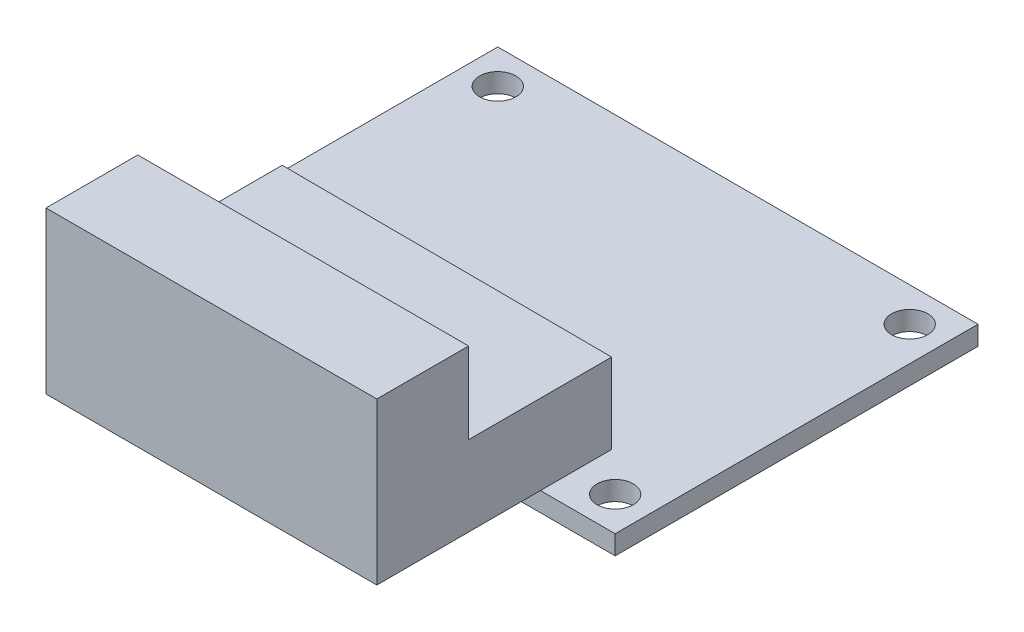
SolidWorks part; units mm, degrees
ref_plane "Front" through (0, 0, 0) normal (0, 0, 1) x (1, 0, 0)
ref_plane "Top" through (0, 0, 0) normal (0, 1, 0) x (1, 0, 0)
ref_plane "Right" through (0, 0, 0) normal (1, 0, 0) x (0, 0, -1)
sketch "Szkic1" plane through (0, 0, 0) normal (0, 1, 0) x (1, 0, 0)
  line L1 (-25.4695, 15.2387) -> (19.5305, 15.2387)
  line L2 (-25.4695, 15.2387) -> (-25.4695, -18.7613)
  line L3 (-25.4695, -18.7613) -> (19.5305, -18.7613)
  line L4 (19.5305, 15.2387) -> (19.5305, -18.7613)
  dimension "D1" = 45
  dimension "D2" = 34
extrude "Dodanie-wyciągnięcie1" add sketch "Szkic1" along normal blind 1.8
sketch "Szkic2" plane through (0, 1.8, 0) normal (0, 1, 0) x (1, 0, 0)
  line L0 (-25.4695, 15.2387) -> (-25.4695, -18.7613) construction
  line L1 (-25.4695, -18.7613) -> (19.5305, -18.7613) construction
  line L2 (-2.9695, -18.7613) -> (-2.9695, 15.2387) construction
  line L3 (19.5305, 15.2387) -> (-25.4695, 15.2387) construction
  line L4 (19.5305, -1.7613) -> (-25.4695, -1.7613) construction
  line L5 (19.5305, -18.7613) -> (19.5305, 15.2387) construction
  circle A0 centre (-22.2695, -15.5613) radius 1.7
  circle A1 centre (16.3305, -15.5613) radius 1.7
  circle A2 centre (16.3305, 12.0387) radius 1.7
  circle A3 centre (-22.2695, 12.0387) radius 1.7
  dimension "D1" = 3.2
  dimension "D2" = 3.2
extrude "Wytnij-wyciągnięcie1" cut sketch "Szkic2" against normal blind 1.8
sketch "Szkic3" plane through (0, 1.8, 0) normal (0, 1, 0) x (1, 0, 0)
  line L0 (-2.9695, -18.7613) -> (-2.9695, 15.2387) construction
  line L1 (-25.4695, -18.7613) -> (19.5305, -18.7613) construction
  line L2 (19.5305, 15.2387) -> (-25.4695, 15.2387) construction
  line L3 (-18.4695, -34.0932) -> (-18.4695, -11.9613)
  line L4 (12.5305, -12.0932) -> (12.5305, -34.0932)
  line L5 (-18.4695, -11.9613) -> (12.5305, -12.0932)
  line L6 (-18.4695, -34.0932) -> (12.5305, -34.0932)
  dimension "D2" = 22
extrude "Dodanie-wyciągnięcie2" add sketch "Szkic3" along normal blind 7.5
sketch "Szkic4" plane through (0, 9.3, 0) normal (0, 1, 0) x (1, 0, 0)
  line L0 (-18.4695, -34.0932) -> (-18.4695, -25.4932)
  line L1 (-18.4695, -25.4932) -> (12.5305, -25.4932)
  line L2 (12.5305, -34.0932) -> (12.5305, -12.0932) construction
  line L3 (12.5305, -25.4932) -> (12.5305, -34.0932)
  line L4 (12.5305, -34.0932) -> (-18.4695, -34.0932)
extrude "Dodanie-wyciągnięcie3" add sketch "Szkic4" along normal blind 7.6
